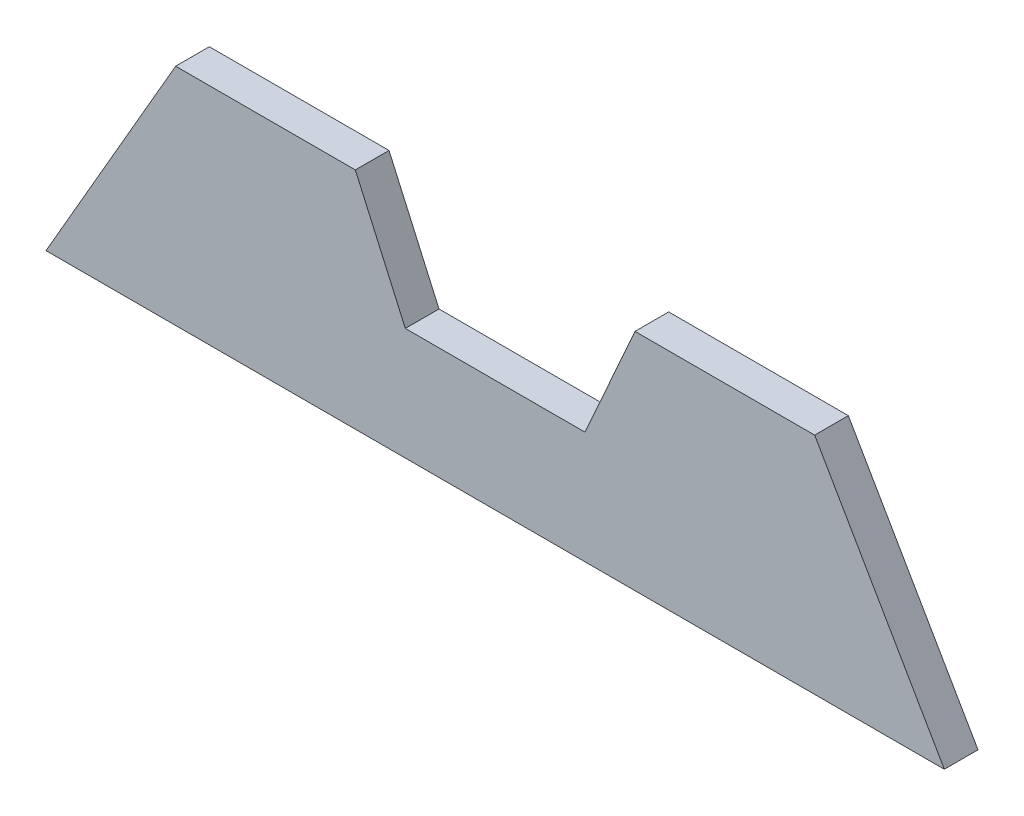
SolidWorks part; units mm, degrees
material "AISI 1045 Steel, cold drawn"
ref_plane "Front Plane" through (0, 0, 0) normal (0, 0, 1) x (1, 0, 0)
ref_plane "Top Plane" through (0, 0, 0) normal (0, 1, 0) x (1, 0, 0)
ref_plane "Right Plane" through (0, 0, 0) normal (1, 0, 0) x (0, 0, -1)
sketch "Sketch2" plane through (0, 0, 0) normal (0, 0, 1) x (1, 0, 0)
  line L0 (0, 0) -> (23.094, 40)
  line L1 (23.094, 40) -> (55.094, 40)
  line L2 (55.094, 40) -> (64, 20)
  line L3 (64, 20) -> (96, 20)
  line L4 (96, 20) -> (104.906, 40)
  line L5 (104.906, 40) -> (136.906, 40)
  line L6 (136.906, 40) -> (160, 0)
  line L7 (160, 0) -> (0, 0)
  point P8 (43.6116, 40)
  point P9 (80, 0)
  point P11 (64.8205, 28.7477)
  point P12 (104.906, 40)
  point P13 (66.0088, 20)
  point P14 (80, 20)
  dimension "D1" = 60
  dimension "D2" = 40
  dimension "D3" = 60
  dimension "D4" = 32
  dimension "D5" = 160
  dimension "D6" = 20
extrude "Boss-Extrude1" add sketch "Sketch2" along normal mid plane 6
equation "\"D3@Sketch2\"=\"D1@Sketch2\""
equation "\"D4@Sketch2\" = \"D5@Sketch2\" / 5"
